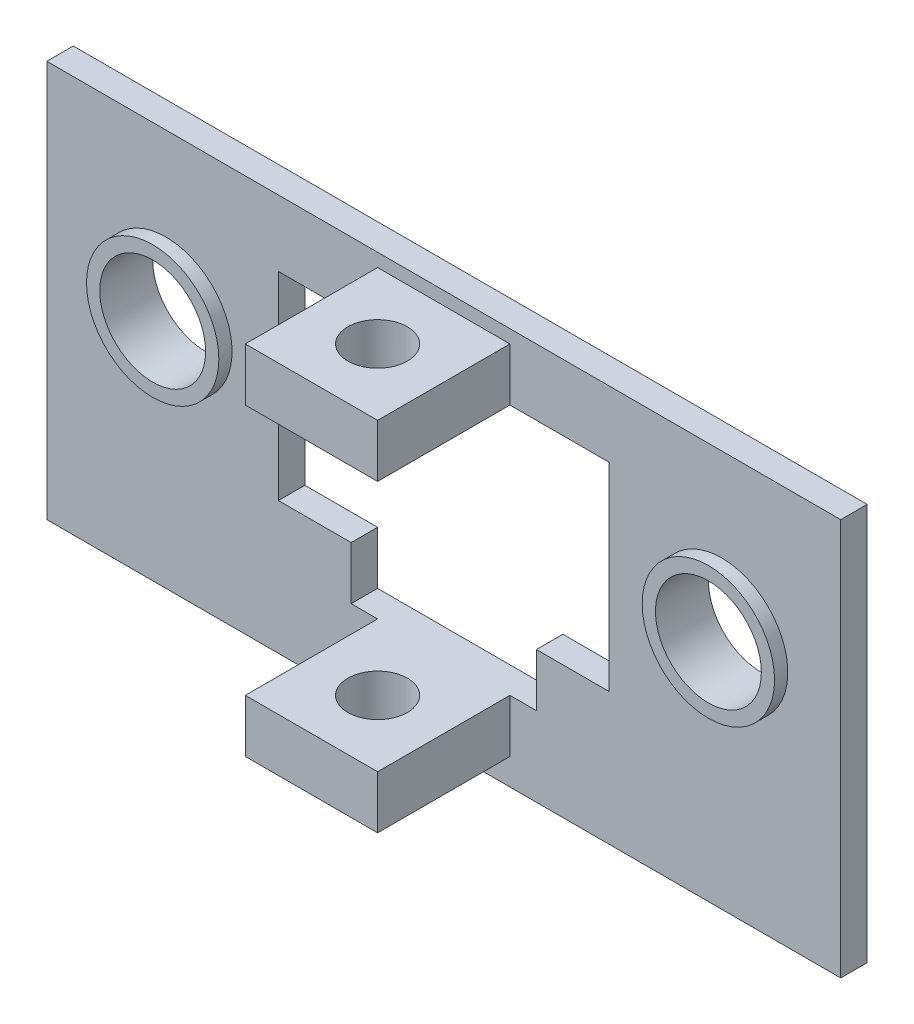
SolidWorks part; units mm, degrees
ref_plane "Front Plane" through (0, 0, 0) normal (0, 0, 1) x (1, 0, 0)
ref_plane "Top Plane" through (0, 0, 0) normal (0, 1, 0) x (1, 0, 0)
ref_plane "Right Plane" through (0, 0, 0) normal (1, 0, 0) x (0, 0, -1)
sketch "Sketch1" plane through (0, 0, 0) normal (0, 0, 1) x (1, 0, 0)
  line L1 (-30, -15) -> (30, -15)
  line L2 (-30, -15) -> (-30, 15)
  line L3 (-30, 15) -> (30, 15)
  line L4 (30, -15) -> (30, 15)
  line L5 (-30, -15) -> (30, 15) construction
  line L6 (-30, 15) -> (30, -15) construction
  point P0 (0, 0)
  dimension "D1" = 60
  dimension "D2" = 30
extrude "Boss-Extrude1" add sketch "Sketch1" along normal blind 2
sketch "Sketch2" plane through (0, 0, 2) normal (0, 0, 1) x (1, 0, 0)
  line L3 (-30, -15) -> (30, -15) construction
  line L4 (-30, 15) -> (-30, -15) construction
  circle A0 centre (-21, 3) radius 4
  circle A1 centre (21, 3) radius 4
  point P4 (0, 0)
  dimension "D1" = 8
  dimension "D2" = 8
  dimension "D3" = 42
  dimension "D4" = 9
  dimension "D5" = 18
extrude "Cut-Extrude1" cut sketch "Sketch2" against normal blind 13
sketch "Sketch3" plane through (0, 0, 2) normal (0, 0, 1) x (1, 0, 0)
  line L5 (-12.5, 10) -> (-12.5, -5)
  line L6 (30, -15) -> (30, 15) construction
  line L9 (12.5, 10) -> (-12.5, 10)
  line L11 (12.5, 10) -> (12.5, -5)
  line L13 (12.5, -5) -> (-12.5, -5)
  line L14 (-30, 15) -> (-30, -15) construction
  point P0 (0, 0)
  dimension "D1" = 25
  dimension "D2" = 17.5
  dimension "D3" = 15
  dimension "D4" = 17.5
extrude "Cut-Extrude2" cut sketch "Sketch3" against normal through all
sketch "Sketch5" plane through (0, 0, 2) normal (0, 0, 1) x (1, 0, 0)
  circle A0 centre (-21, 3) radius 5
  circle A1 centre (-21, 3) radius 4
  circle A2 centre (21, 3) radius 5
  circle A3 centre (21, 3) radius 4
  dimension "D1" = 8
  dimension "D2" = 8
  dimension "D3" = 10
  dimension "D4" = 10
extrude "Boss-Extrude2" add sketch "Sketch5" along normal blind 1
sketch "Sketch7" plane through (0, 0, 0) normal (0, 0, -1) x (-1, 0, 0)
  line L0 (-30, 15) -> (30, 15) construction
  circle A0 centre (-21, 3) radius 5
  circle A1 centre (-21, 3) radius 4
  circle A2 centre (21, 3) radius 5
  circle A3 centre (21, 3) radius 4
  dimension "D1" = 8
  dimension "D2" = 8
  dimension "D4" = 10
  dimension "D5" = 10
  dimension "D3" = 12
extrude "Boss-Extrude3" add sketch "Sketch7" along normal blind 1
sketch "Sketch9" plane through (0, 0, 2) normal (0, 0, 1) x (1, 0, 0)
  line L0 (-30, 15) -> (-30, -15) construction
  line L1 (-5, -9) -> (5, -9)
  line L2 (-5, -9) -> (-5, -13)
  line L3 (-5, -13) -> (5, -13)
  line L4 (5, -9) -> (5, -13)
  line L5 (-30, -15) -> (30, -15) construction
  line L6 (30, 15) -> (-30, 15) construction
  line L7 (-5, 14) -> (5, 14)
  line L8 (-5, 14) -> (-5, 10)
  line L9 (-5, 10) -> (5, 10)
  line L10 (5, 14) -> (5, 10)
  line L11 (-30, 15) -> (-30, -15) construction
  dimension "D1" = 10
  dimension "D2" = 4
  dimension "D3" = 25
  dimension "D4" = 2
  dimension "D5" = 10
  dimension "D6" = 4
  dimension "D7" = 1
  dimension "D8" = 25
extrude "Boss-Extrude4" add sketch "Sketch9" along normal blind 10
sketch "Sketch10" plane through (0, 10, 0) normal (0, -1, 0) x (1, 0, 0)
  line L0 (5, 12) -> (5, 2) construction
  line L3 (-5, 12) -> (5, 12) construction
  circle A0 centre (0, 7) radius 2.25
  point P4 (0, 0)
  point P7 (-0.7819, 12)
  point P8 (-0.5572, 12)
  dimension "D1" = 4.5
  dimension "D3" = 5
  dimension "D2" = 5
extrude "Cut-Extrude3" cut sketch "Sketch10" against normal through all
sketch "Sketch11" plane through (0, -13, 0) normal (0, -1, 0) x (1, 0, 0)
  line L0 (5, 12) -> (5, 2) construction
  line L1 (-5, 12) -> (5, 12) construction
  circle A0 centre (0, 7) radius 2.25
  dimension "D1" = 4.5
  dimension "D3" = 5
  dimension "D2" = 5
extrude "Cut-Extrude4" cut sketch "Sketch11" against normal through all
sketch "Sketch13" plane through (0, 0, 2) normal (0, 0, 1) x (1, 0, 0)
  line L0 (-12.5, -5) -> (12.5, -5) construction
  line L1 (-7, -5) -> (7, -5)
  line L2 (-7, -5) -> (-7, -9)
  line L3 (-7, -9) -> (7, -9)
  line L4 (7, -5) -> (7, -9)
  line L6 (30, -15) -> (30, 15) construction
  line L7 (-30, 15) -> (-30, -15) construction
  dimension "D1" = 14
  dimension "D2" = 23
  dimension "D3" = 23
  dimension "D4" = 4
extrude "Cut-Extrude6" cut sketch "Sketch13" against normal through all
